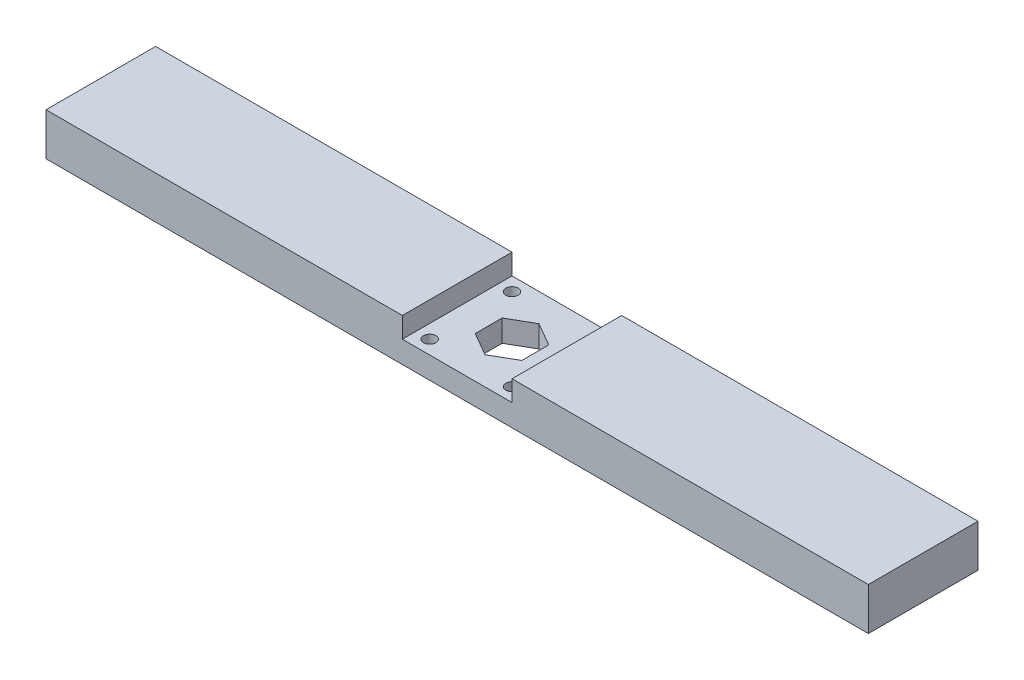
SolidWorks part; units mm, degrees
ref_plane "Front Plane" through (0, 0, 0) normal (0, 0, 1) x (1, 0, 0)
ref_plane "Top Plane" through (0, 0, 0) normal (0, 1, 0) x (1, 0, 0)
ref_plane "Right Plane" through (0, 0, 0) normal (1, 0, 0) x (0, 0, -1)
sketch "Sketch1" plane through (0, 0, 0) normal (0, 0, 1) x (1, 0, 0)
  line L0 (0, 104.1848) -> (0, -100.9565) construction
  line L1 (-150, 7.75) -> (-150, -7.75)
  line L2 (-150, -7.75) -> (150, -7.75)
  line L3 (-150, 7.75) -> (-20, 7.75)
  line L4 (-20, 7.75) -> (-20, 0.25)
  line L5 (-20, 0.25) -> (20, 0.25)
  line L6 (150, 7.75) -> (150, -7.75)
  line L7 (20, 7.75) -> (20, 0.25)
  line L8 (150, 7.75) -> (20, 7.75)
  point P5 (-150, 0)
  point P12 (0, -7.75)
  point P14 (0, 0.25)
  dimension "D1" = 300
  dimension "D2" = 15.5
  dimension "D3" = 7.5
  dimension "D4" = 40
extrude "Boss-Extrude1" add sketch "Sketch1" along normal mid plane 40
sketch "Sketch2" plane through (0, 0.25, 0) normal (0, 1, 0) x (1, 0, 0)
  line L0 (-3.5, 3.5) -> (-1.225, 3.5) construction
  line L1 (-3.5, 10) -> (3.5, 10) construction
  line L2 (-3.5, 10) -> (-3.5, 3.5) construction
  line L3 (-3.5, -10) -> (3.5, -10) construction
  line L4 (3.5, 10) -> (3.5, 3.5) construction
  line L5 (-3.5, 10) -> (3.5, -10) construction
  line L6 (-3.5, -10) -> (3.5, 10) construction
  line L7 (-10, 3.5) -> (-3.5, 3.5) construction
  line L8 (-10, 3.5) -> (-10, -3.5) construction
  line L9 (-10, -3.5) -> (-3.5, -3.5) construction
  line L10 (10, 3.5) -> (10, -3.5) construction
  line L11 (-10, 3.5) -> (10, -3.5) construction
  line L12 (-10, -3.5) -> (10, 3.5) construction
  line L13 (-1.225, 3.5) -> (1.225, 3.5) construction
  line L14 (-3.5, 3.5) -> (-3.5, 1.225) construction
  line L15 (-3.5, -3.5) -> (-3.5, -10) construction
  line L16 (-3.5, 1.225) -> (-3.5, -1.225) construction
  line L17 (-3.5, -1.225) -> (-3.5, -3.5) construction
  line L18 (-3.5, -3.5) -> (-1.225, -3.5) construction
  line L19 (3.5, -3.5) -> (10, -3.5) construction
  line L20 (-1.225, -3.5) -> (1.225, -3.5) construction
  line L21 (1.225, -3.5) -> (3.5, -3.5) construction
  line L22 (3.5, -1.225) -> (3.5, -3.5) construction
  line L23 (3.5, -3.5) -> (3.5, -10) construction
  line L24 (3.5, 1.225) -> (3.5, -1.225) construction
  line L25 (3.5, 3.5) -> (3.5, 1.225) construction
  line L26 (1.225, 3.5) -> (3.5, 3.5) construction
  line L27 (3.5, 3.5) -> (10, 3.5) construction
  line L28 (0, 16.757) -> (0, -13.5066) construction
  line L29 (-13.5311, 0) -> (11.9505, 0) construction
  line L31 (0, -9.815) -> (8.5, -4.9075)
  line L32 (8.5, -4.9075) -> (8.5, 4.9075)
  line L33 (8.5, 4.9075) -> (0, 9.815)
  line L34 (0, 9.815) -> (-8.5, 4.9075)
  line L35 (-8.5, 4.9075) -> (-8.5, -4.9075)
  line L36 (-8.5, -4.9075) -> (0, -9.815)
  circle A0 centre (15.015, 15) radius 2.25
  circle A1 centre (-15.015, 15) radius 2.25
  circle A2 centre (15.015, -15) radius 2.25
  circle A3 centre (-15.015, -15) radius 2.25
  circle A4 centre (0, 0) radius 8.5 construction
  circle A5 centre (0, 0) radius 5.25 construction
  point P0 (0, 0)
  point P5 (0, 0)
  dimension "D5" = 15
  dimension "D7" = 4.5
  dimension "D9" = 10.5
  dimension "D1" = 7
  dimension "D2" = 20
  dimension "D3" = 7
  dimension "D4" = 20
  dimension "D6" = 15.015
  dimension "D8" = 17
extrude "Cut-Extrude1" cut sketch "Sketch2" against normal blind 40
